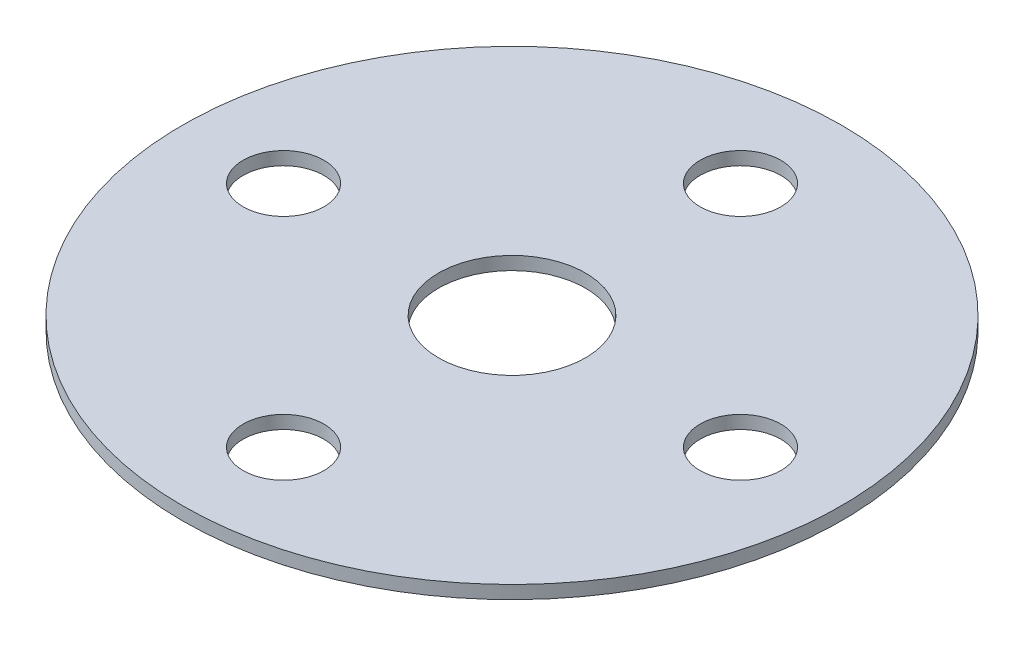
SolidWorks part; units mm, degrees
material "201 Annealed Stainless Steel (SS)"
ref_plane "Front Plane" through (0, 0, 0) normal (0, 0, 1) x (1, 0, 0)
ref_plane "Top Plane" through (0, 0, 0) normal (0, 1, 0) x (1, 0, 0)
ref_plane "Right Plane" through (0, 0, 0) normal (1, 0, 0) x (0, 0, -1)
sketch "Sketch1" plane through (0, 0, 0) normal (0, 1, 0) x (1, 0, 0)
  circle A0 centre (0, 0) radius 21.6364
  circle A1 centre (0, 0) radius 4.826
  circle A2 centre (0, 15) radius 2.65
  circle A3 centre (15, 0) radius 2.65
  circle A4 centre (0, -15) radius 2.65
  circle A5 centre (-15, 0) radius 2.65
  point P15 (0, 0)
  dimension "D1" = 43.2728
  dimension "D2" = 9.652
  dimension "D3" = 5.3
  dimension "D4" = 15
  dimension "D5" = 4
extrude "Boss-Extrude1" add sketch "Sketch1" along normal blind 0.8636
